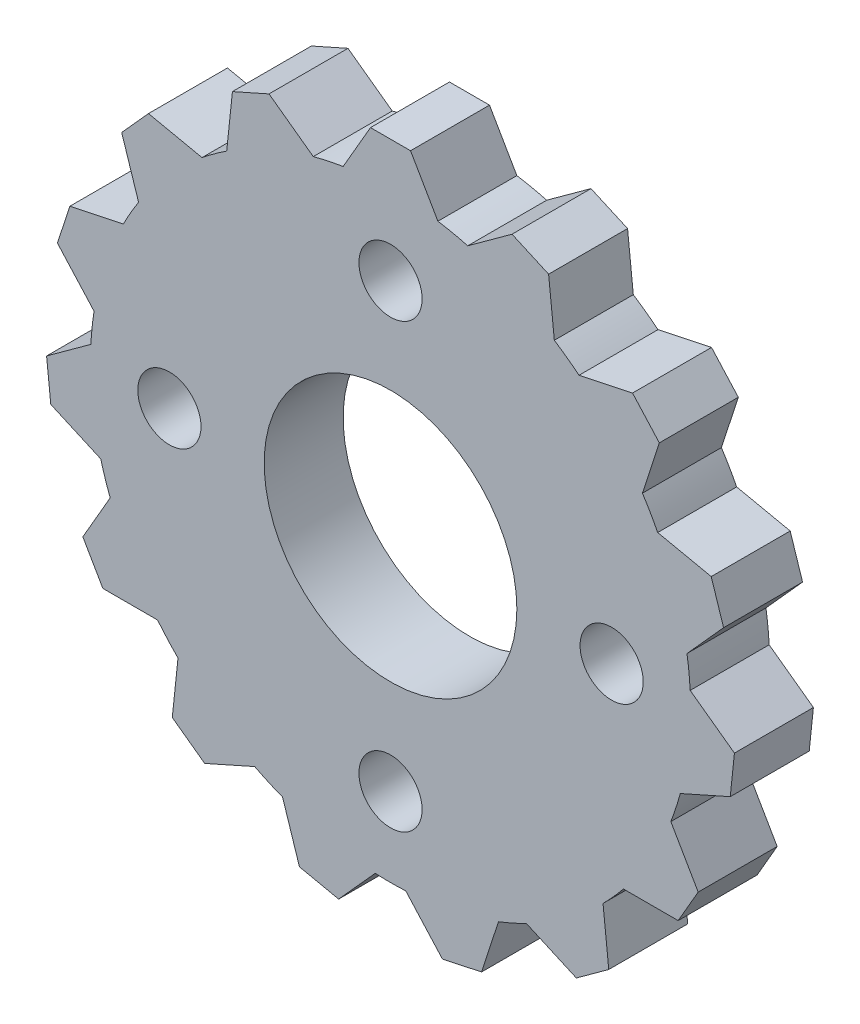
SolidWorks part; units mm, degrees
ref_plane "Front Plane" through (0, 0, 0) normal (0, 0, 1) x (1, 0, 0)
ref_plane "Top Plane" through (0, 0, 0) normal (0, 1, 0) x (1, 0, 0)
ref_plane "Right Plane" through (0, 0, 0) normal (1, 0, 0) x (0, 0, -1)
sketch "Sketch1" plane through (0, 0, 0) normal (0, 0, 1) x (1, 0, 0)
  circle A0 centre (0, 0) radius 9.5
  circle A1 centre (0, 0) radius 4
  circle A2 centre (0, 0) radius 7 construction
  circle A3 centre (0, 7) radius 1
  circle A4 centre (7, 0) radius 1
  circle A5 centre (0, -7) radius 1
  circle A6 centre (-7, 0) radius 1
  point P16 (0, 0)
  dimension "D1" = 8
  dimension "D2" = 19
  dimension "D3" = 14
  dimension "D4" = 2
  dimension "D5" = 4
extrude "Boss-Extrude1" add sketch "Sketch1" along normal blind 2.5
sketch "Sketch2" plane through (0, 0, 0) normal (0, 0, 1) x (1, 0, 0)
  line L0 (-1.5, 9.3808) -> (-0.634, 10.8808)
  line L1 (-0.634, 10.8808) -> (0.634, 10.8808)
  line L2 (0, -1.375) -> (0, 1.375) construction
  line L4 (1.5, 9.3808) -> (-1.5, 9.3808)
  line L5 (1.5, 9.3808) -> (0.634, 10.8808)
  circle A0 centre (0, 0) radius 9.5 construction
  point P10 (0, 9.3808)
  point P11 (0, 10.8808)
  dimension "D1" = 1.5
  dimension "D2" = 1.5
  dimension "D3" = 60
extrude "Boss-Extrude2" add sketch "Sketch2" along normal blind 2.5
pattern_circular "CirPattern1" count 15 every 24 about axis through (0, 0, 0) along (0, 0, 1) of "Boss-Extrude2"
